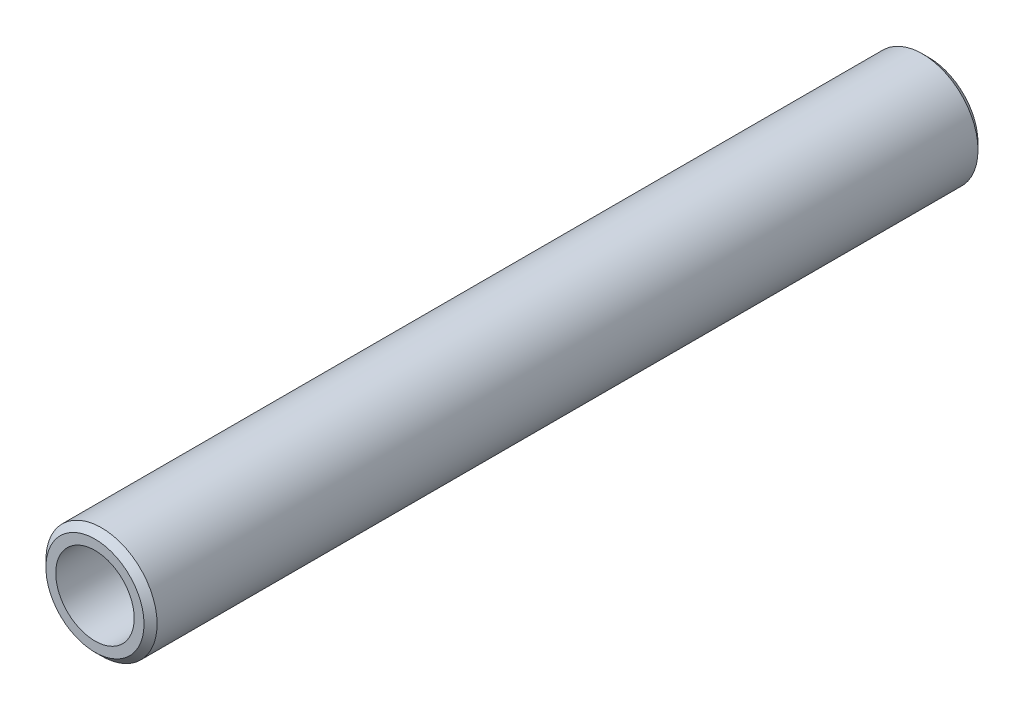
SolidWorks part; units mm, degrees
ref_plane "Front Plane" through (0, 0, 0) normal (0, 0, 1) x (1, 0, 0)
ref_plane "Top Plane" through (0, 0, 0) normal (0, 1, 0) x (1, 0, 0)
ref_plane "Right Plane" through (0, 0, 0) normal (1, 0, 0) x (0, 0, -1)
sketch "Sketch1" plane through (0, 0, 0) normal (0, 0, 1) x (1, 0, 0)
  circle A0 centre (0, 0) radius 12
  circle A1 centre (0, 0) radius 17
  dimension "D1" = 34
  dimension "D2" = 24
extrude "Boss-Extrude1" add sketch "Sketch1" along normal blind 255 contours A1 A0
chamfer "Chamfer1" distance 2 angle 45 2 edges at (17, 0, 0) (17, 0, 255)
